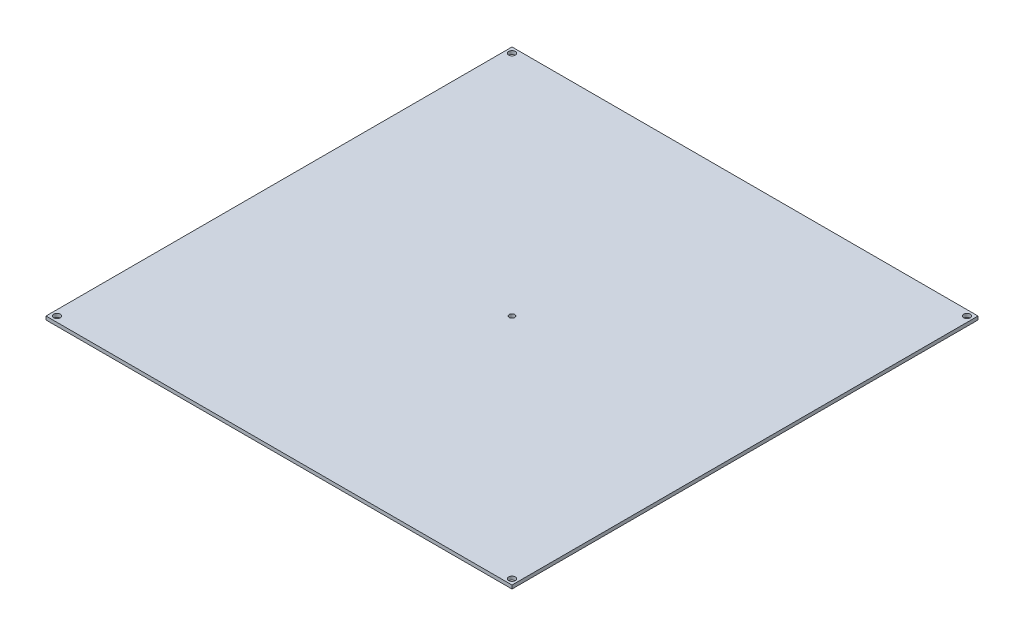
SolidWorks part; units mm, degrees
material "Silicon"
ref_plane "Front Plane" through (0, 0, 0) normal (0, 0, 1) x (1, 0, 0)
ref_plane "Top Plane" through (0, 0, 0) normal (0, 1, 0) x (1, 0, 0)
ref_plane "Right Plane" through (0, 0, 0) normal (1, 0, 0) x (0, 0, -1)
sketch "Sketch1" plane through (0, 0, 0) normal (0, 1, 0) x (1, 0, 0)
  line L1 (-107, 107) -> (107, 107)
  line L2 (-107, 107) -> (-107, -107)
  line L3 (-107, -107) -> (107, -107)
  line L4 (107, 107) -> (107, -107)
  line L5 (-107, 107) -> (107, -107) construction
  line L6 (-107, -107) -> (107, 107) construction
  point P0 (0, 0)
  dimension "D1" = 214
  dimension "D2" = 214
extrude "Boss-Extrude1" add sketch "Sketch1" along normal blind 1.6
sketch "Sketch2" plane through (0, 1.6, 0) normal (0, 1, 0) x (1, 0, 0)
  line L0 (0, 107) -> (0, -107) construction
  line L1 (107, 107) -> (-107, 107) construction
  line L2 (-107, -107) -> (107, -107) construction
  line L3 (107, 0) -> (-107, 0) construction
  line L4 (107, -107) -> (107, 107) construction
  line L5 (-107, 107) -> (-107, -107) construction
  circle A0 centre (-104.5, 104.5) radius 1.5
  circle A1 centre (104.5, 104.5) radius 1.5
  circle A2 centre (104.5, -104.5) radius 1.5
  circle A3 centre (-104.5, -104.5) radius 1.5
  circle A4 centre (0, 0) radius 1.25
  dimension "D1" = 3
  dimension "D4" = 2.5
  dimension "D2" = 2.5
  dimension "D3" = 2.5
extrude "Cut-Extrude1" cut sketch "Sketch2" against normal through all
equation "\"D3@Sketch2\" = \"D2@Sketch2\""
